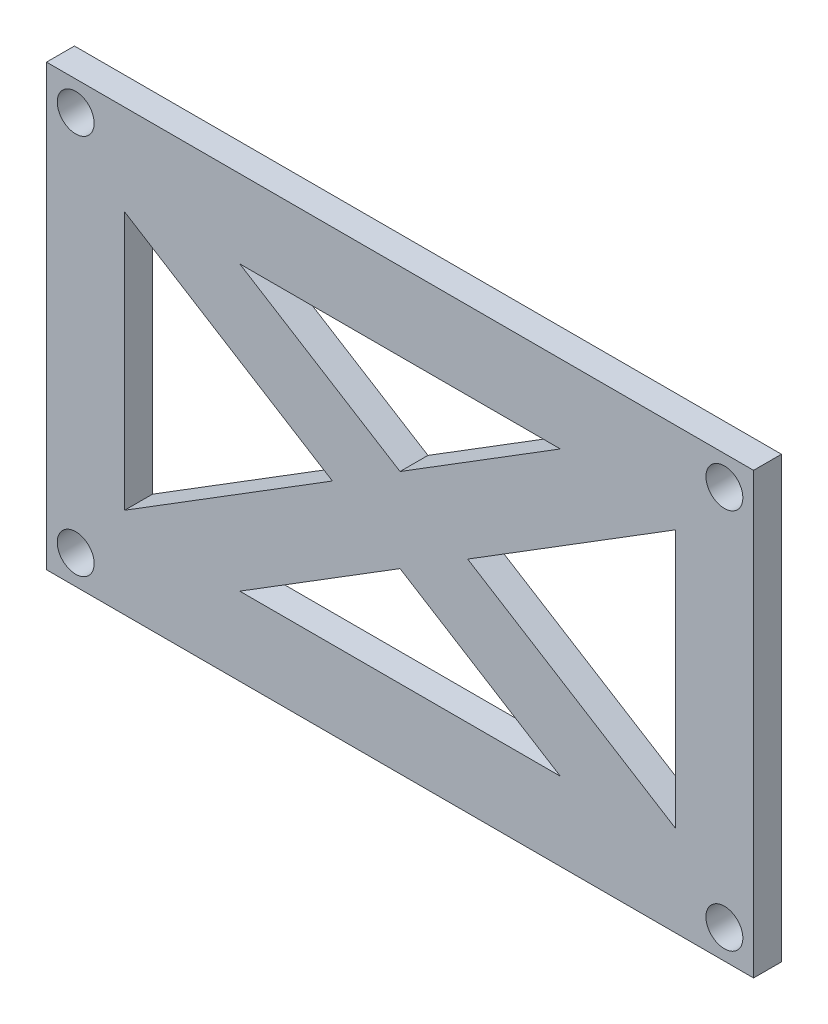
SolidWorks part; units mm, degrees
material "Delrin"
ref_plane "Front Plane" through (0, 0, 0) normal (0, 0, 1) x (1, 0, 0)
ref_plane "Top Plane" through (0, 0, 0) normal (0, 1, 0) x (1, 0, 0)
ref_plane "Right Plane" through (0, 0, 0) normal (1, 0, 0) x (0, 0, -1)
sketch "Sketch2" plane through (0, 0, 0) normal (0, 0, 1) x (1, 0, 0)
  line L0 (15.6718, -7.3526) -> (3.848, 0)
  line L1 (20.1168, 12.5095) -> (-20.1168, 12.5095)
  line L2 (20.1168, 12.5095) -> (20.1168, -12.5095)
  line L3 (20.1168, -12.5095) -> (-20.1168, -12.5095)
  line L4 (-20.1168, 12.5095) -> (-20.1168, -12.5095)
  line L5 (20.1168, 12.5095) -> (-20.1168, -12.5095) construction
  line L6 (20.1168, -12.5095) -> (-20.1168, 12.5095) construction
  line L7 (9.1207, -8.0645) -> (0, -2.3928)
  line L8 (9.1207, 8.0645) -> (-9.1207, 8.0645)
  line L9 (-15.6718, 7.3526) -> (-15.6718, -7.3526)
  line L10 (9.1207, -8.0645) -> (-9.1207, -8.0645)
  line L11 (15.6718, 7.3526) -> (15.6718, -7.3526)
  line L12 (21.1898, -10.7839) -> (-19.0438, 14.2351) construction
  line L13 (19.0438, -14.2351) -> (-21.1898, 10.7839) construction
  line L14 (-15.6718, 8.0645) -> (-15.6718, -8.0645) construction
  line L15 (15.6718, 8.0645) -> (-15.6718, 8.0645) construction
  line L16 (15.6718, 8.0645) -> (15.6718, -8.0645) construction
  line L17 (15.6718, -8.0645) -> (-15.6718, -8.0645) construction
  line L18 (9.1207, 8.0645) -> (0, 2.3928)
  line L19 (15.6718, 7.3526) -> (3.848, 0)
  line L20 (21.1898, 10.7839) -> (-19.0438, -14.2351) construction
  line L21 (19.0438, 14.2351) -> (-21.1898, -10.7839) construction
  line L22 (-3.848, 0) -> (-15.6718, -7.3526)
  line L23 (-3.848, 0) -> (-15.6718, 7.3526)
  line L24 (0, -2.3928) -> (-9.1207, -8.0645)
  line L25 (0, 2.3928) -> (-9.1207, 8.0645)
  line L26 (0, -1000) -> (0, 49000) construction
  line L27 (-1000, 0) -> (49000, 0) construction
  circle A0 centre (-18.4568, 10.8495) radius 1.05
  circle A1 centre (-18.4568, -10.8495) radius 1.05
  circle A2 centre (18.4568, -10.8495) radius 1.05
  circle A3 centre (18.4568, 10.8495) radius 1.05
  point P0 (0, 0)
  dimension "D10" = 2.1
  dimension "D1" = 40.2336
  dimension "D2" = 25.019
  dimension "D8" = 1.66
  dimension "D9" = 1.66
  dimension "D3" = 2.032
  dimension "D4" = 2.032
  dimension "D5" = 4.445
  dimension "D6" = 2.032
  dimension "D7" = 2.032
extrude "Boss-Extrude1" add sketch "Sketch2" along normal blind 1.5875
